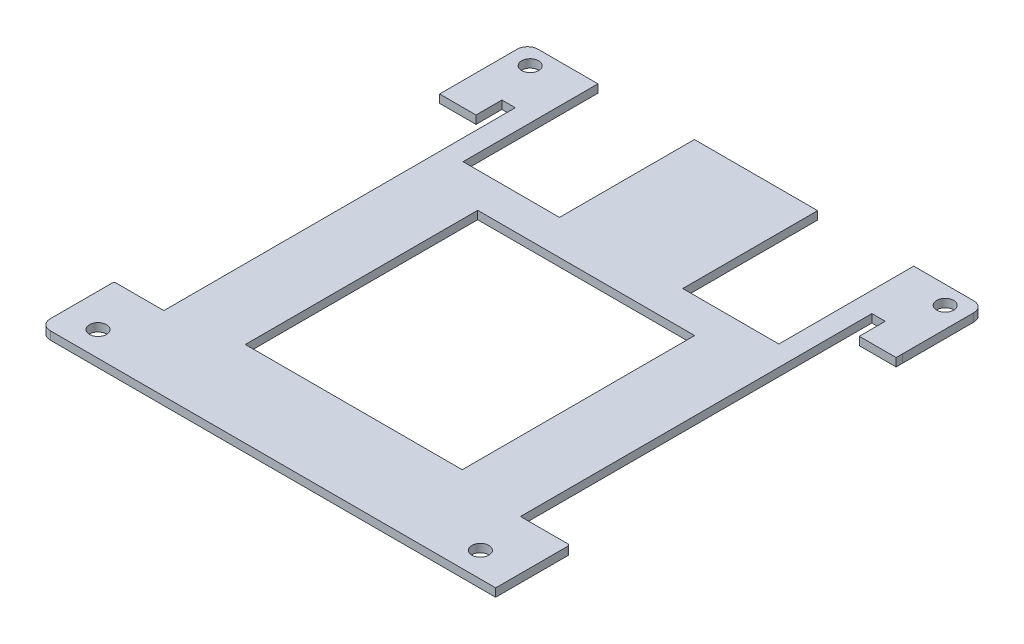
SolidWorks part; units mm, degrees
material "Copper"
ref_plane "Front Plane" through (0, 0, 0) normal (0, 0, 1) x (1, 0, 0)
ref_plane "Top Plane" through (0, 0, 0) normal (0, 1, 0) x (1, 0, 0)
ref_plane "Right Plane" through (0, 0, 0) normal (1, 0, 0) x (0, 0, -1)
sketch "Sketch1" plane through (0, 0, 0) normal (0, 1, 0) x (1, 0, 0)
  line L0 (-44, 45) -> (-44, 29.1624)
  line L1 (-43.6121, 28.7745) -> (-33.2119, 28.7745)
  line L2 (-42, 47) -> (42, 47)
  line L3 (44, 45) -> (44, 31.284)
  line L4 (32.8228, 27.7745) -> (32.8228, -30.4694)
  line L5 (26.2188, 17.9319) -> (-33.6927, 17.9319) construction
  line L6 (33.8228, 28.7745) -> (43.6111, 28.7745)
  line L7 (43.8497, -38.27) -> (43.8497, -47)
  line L8 (42.7059, -47) -> (-42, -47)
  line L9 (-44, -45) -> (-44, -38.977)
  line L10 (-32.824, 28.3866) -> (-32.824, -32.3056)
  line L11 (33.824, -32.6935) -> (36.0988, -32.6935)
  line L12 (23.409, -31.5) -> (-23.409, -31.5)
  line L13 (-23.409, -31.5) -> (-23.409, 13.2954)
  line L14 (-23.409, 13.2954) -> (-12.909, 13.2954)
  line L15 (-12.909, 13.2954) -> (-12.909, 25.9954)
  line L16 (-12.909, 25.9954) -> (12.909, 25.9954)
  line L17 (12.909, 25.9954) -> (12.909, 13.2954)
  line L18 (12.909, 13.2954) -> (23.409, 13.2954)
  line L19 (23.409, 13.2954) -> (23.409, -31.5)
  line L20 (43.8497, -38.27) -> (43.8497, -33.0814)
  line L21 (43.4618, -32.6935) -> (36.0988, -32.6935)
  line L22 (43.8497, -47) -> (42.7059, -47)
  line L23 (-44, 28.7745) -> (52.9697, 28.7745) construction
  line L24 (44, 31.284) -> (43.999, 29.1622)
  line L25 (-33.2119, -32.6935) -> (-36.1, -32.6935)
  line L26 (-44, -38.977) -> (-44, -33.0814)
  line L27 (-43.6121, -32.6935) -> (-36.1, -32.6935)
  line L28 (32.8228, -30.4694) -> (32.8228, -32.6935)
  line L29 (32.8228, -32.6935) -> (33.824, -32.6935)
  circle A0 centre (40, 43.5) radius 1.6383
  circle A1 centre (-40, 43.5) radius 1.6383
  circle A2 centre (-37.6, -42.2) radius 1.6383
  circle A3 centre (36.1, -42.2) radius 1.6383
  arc A5 (-42, 47) -> (-44, 45) centre (-42, 45) ccw
  arc A6 (44, 45) -> (42, 47) centre (42, 45) ccw
  arc A7 (-32.824, -32.3056) -> (-33.2119, -32.6935) centre (-33.2119, -32.3056) cw
  arc A10 (-33.2119, 28.7745) -> (-32.824, 28.3866) centre (-33.2119, 28.3866) cw
  arc A11 (-44, -45) -> (-42, -47) centre (-42, -45) ccw
  arc A12 (-44, 29.1624) -> (-43.6121, 28.7745) centre (-43.6121, 29.1624) ccw
  arc A13 (43.999, 29.1622) -> (43.6111, 28.7745) centre (43.6111, 29.1624) cw
  arc A14 (43.8497, -33.0814) -> (43.4618, -32.6935) centre (43.4618, -33.0814) ccw
  arc A15 (-44, -33.0814) -> (-43.6121, -32.6935) centre (-43.6121, -33.0814) cw
  arc A16 (33.8228, 28.7745) -> (32.8228, 27.7745) centre (33.8228, 27.7745) ccw
  point P27 (32.8228, -32.6935)
  point P51 (-32.824, -32.6935)
  point P54 (-32.824, 28.7745)
  point P60 (43.9988, 28.7745)
  point P67 (32.8228, 28.7745)
  dimension "D24" = 61.468
  dimension "D3" = 80
  dimension "D8" = 3.2766
  dimension "D22" = 1
  dimension "D2" = 6.4
  dimension "D4" = 44.7954
  dimension "D5" = 12.7
  dimension "D6" = 44.7954
  dimension "D7" = 3.5
  dimension "D9" = 4
  dimension "D10" = 3.5
  dimension "D11" = 85.7
  dimension "D12" = 85.7
  dimension "D13" = 21.0046
  dimension "D14" = 11.176
  dimension "D15" = 84
  dimension "D16" = 25.818
  dimension "D17" = 12.7
  dimension "D18" = 46.818
  dimension "D19" = 10.5
  dimension "D20" = 10.5
  dimension "D21" = 73.7
  dimension "D23" = 13.716
  dimension "D26" = 6.604
  dimension "D29" = 11.176
  dimension "D30" = 61.468
  dimension "D31" = 3.276
  dimension "D32" = 3.276
extrude "Boss-Extrude1" add sketch "Sketch1" along normal blind 1.575
sketch "Sketch2" plane through (0, 1.575, 0) normal (0, 1, 0) x (1, 0, 0)
  line L0 (-12.909, 19.06) -> (-30.435, 19.06)
  line L1 (42, 47) -> (-42, 47) construction
  line L2 (-12.909, 25.9954) -> (12.909, 25.9954) construction
  line L3 (-30.435, 47) -> (30.435, 47)
  line L4 (12.909, 13.2954) -> (12.909, 25.9954) construction
  line L5 (12.909, 19.06) -> (30.435, 19.06)
  line L6 (30.435, 19.06) -> (30.435, 47)
  line L7 (0, 47) -> (0, -47) construction
  line L8 (-42, -47) -> (43.8497, -47) construction
  line L9 (-12.909, 25.9954) -> (-12.909, 19.06)
  line L10 (-30.435, 19.06) -> (-30.435, 47)
  line L11 (12.909, 25.9954) -> (12.909, 19.06)
  line L13 (-12.909, 25.9954) -> (12.909, 25.9954)
  dimension "D1" = 27.94
  dimension "D2" = 17.526
extrude "Cut-Extrude1" cut sketch "Sketch2" against normal blind 2.54
sketch "Sketch16" plane through (0, 1.575, 0) normal (0, 1, 0) x (1, 0, 0)
  line L0 (-42, 47) -> (42, 47) construction
  line L1 (12.909, 19.06) -> (12.909, 13.2954)
  line L2 (12.909, 13.2954) -> (-12.909, 13.2954)
  line L3 (-11.8389, 47) -> (-11.8389, 21)
  line L4 (-30.435, 21) -> (-11.8389, 21)
  line L5 (11.909, 21) -> (11.909, 47)
  line L6 (11.909, 47) -> (-11.8389, 47)
  line L7 (-30.435, 47) -> (-30.435, 19.06) construction
  line L9 (-12.909, 19.06) -> (-12.909, 13.2954)
  line L10 (-30.435, 47) -> (-42, 47) construction
  line L11 (11.909, 21) -> (30.435, 21)
  line L12 (30.435, 19.06) -> (30.435, 47) construction
  line L13 (30.435, 21) -> (30.435, 19.06)
  line L14 (30.435, 19.06) -> (12.909, 19.06)
  line L15 (-30.435, 21) -> (-30.435, 19.06)
  line L16 (-30.435, 19.06) -> (-12.909, 19.06)
  dimension "D1" = 26
extrude "Cutouts for Thruster Heads" add sketch "Sketch16" against normal blind 1.575
sketch "Sketch17" plane through (0, 1.575, 0) normal (0, 1, 0) x (1, 0, 0)
  line L2 (-42.6204, -10.5244) -> (-42.6204, -23.1918)
  line L3 (-42.6204, -23.1918) -> (43.1801, -23.1918)
  line L4 (43.1801, -10.5244) -> (43.1801, -23.1918)
  line L6 (-42.6204, -10.5244) -> (-42.6204, 5.0143)
  line L7 (-42.6204, 5.0143) -> (43.1801, 5.0143)
  line L8 (43.1801, -10.5244) -> (43.1801, 5.0143)
sketch "Sketch18" plane through (0, 1.575, 0) normal (0, 1, 0) x (1, 0, 0)
  line L1 (33.4307, -29.0671) -> (45.3514, -29.0671)
  line L2 (33.4307, -29.0671) -> (33.4307, -32.653)
  line L3 (33.4307, -32.653) -> (45.3514, -32.653)
  line L4 (45.3514, -29.0671) -> (45.3514, -32.653)
  dimension "D1" = 14.347
  dimension "D2" = 10.419
sketch "Sketch21" [suppressed] plane through (0, 1.575, 0) normal (0, 1, 0) x (1, 0, 0)
  line L0 (-32.824, 28.3866) -> (-32.824, -32.3056) construction
  line L1 (-32.824, -23.1918) -> (32.8228, -23.1918)
  line L2 (-32.824, -23.1918) -> (-32.824, -25.8658)
  line L3 (-32.824, -25.8658) -> (32.8228, -25.8658)
  line L4 (32.8228, -23.1918) -> (32.8228, -25.8658)
  dimension "D1" = 2.674
sketch "Sketch20" plane through (0, 1.575, 0) normal (0, 1, 0) x (1, 0, 0)
sketch "Notch for BPR (TOP VIEW)" plane through (0, 1.575, 0) normal (0, 1, 0) x (1, 0, 0)
  line L0 (-43.6121, 28.7745) -> (-33.2119, 28.7745) construction
  line L1 (-36.984, 35.0445) -> (-34.409, 35.0445)
  line L2 (-36.984, 35.0445) -> (-36.984, 28.7745)
  line L3 (-36.984, 28.7745) -> (-34.409, 28.7745)
  line L4 (-34.409, 35.0445) -> (-34.409, 28.7745)
  line L6 (-44, 45) -> (-44, 29.1624) construction
  dimension "D1" = 7.016
  dimension "D2" = 2.575
  dimension "D3" = 6.27
extrude "Cut-Extrude11" cut sketch "Notch for BPR (TOP VIEW)" against normal blind 10
sketch "Notch for BPL (TOP VIEW)" plane through (0, 1.575, 0) normal (0, 1, 0) x (1, 0, 0)
  line L0 (33.8228, 28.7745) -> (43.6111, 28.7745) construction
  line L1 (34.3242, 35.0445) -> (36.8992, 35.0445)
  line L2 (34.3242, 35.0445) -> (34.3242, 28.7745)
  line L3 (34.3242, 28.7745) -> (36.8992, 28.7745)
  line L4 (36.8992, 35.0445) -> (36.8992, 28.7745)
  line L5 (44, 31.284) -> (44, 45) construction
  dimension "D1" = 2.575
  dimension "D2" = 7.1008
extrude "Cut-Extrude12" cut sketch "Notch for BPL (TOP VIEW)" against normal through all
sketch "Sketch22" plane through (0, 1.575, 0) normal (0, 1, 0) x (1, 0, 0)
  line L0 (-32.824, -32.3056) -> (-32.824, -38.5911) construction
  line L1 (34.3242, 28.7745) -> (32.8228, 28.7745)
  line L2 (34.3242, 28.7745) -> (34.3242, -32.6935)
  line L3 (34.3242, -32.6935) -> (32.8228, -32.6935)
  line L4 (32.8228, 28.7745) -> (32.8228, -32.6935)
  line L5 (-33.2119, -32.6935) -> (-31.5595, -32.6935) construction
  line L7 (-32.824, -32.6935) -> (-34.409, -32.6935)
  line L8 (-32.824, -32.6935) -> (-32.824, 28.7745)
  line L9 (-32.824, 28.7745) -> (-34.409, 28.7745)
  line L10 (-34.409, -32.6935) -> (-34.409, 28.7745)
extrude "Boss-Extrude2" add sketch "Sketch22" against normal blind 1.575
sketch "Sketch23" plane through (0, 1.575, 0) normal (0, 1, 0) x (1, 0, 0)
  line L0 (43.999, 29.1622) -> (44, 31.284) construction
  line L1 (36.8992, 28.7745) -> (43.9994, 28.7745)
  line L2 (36.8992, 28.7745) -> (36.8992, 30.0445)
  line L3 (36.8992, 30.0445) -> (43.9994, 30.0445)
  line L4 (43.9994, 28.7745) -> (43.9994, 30.0445)
  line L5 (-44, 45) -> (-44, 29.1624) construction
  line L6 (-36.984, 28.7745) -> (-44, 28.7745)
  line L7 (-36.984, 28.7745) -> (-36.984, 30.0445)
  line L8 (-36.984, 30.0445) -> (-44, 30.0445)
  line L9 (-44, 28.7745) -> (-44, 30.0445)
  dimension "D1" = 1.27
  dimension "D2" = 1.27
extrude "Cut-Extrude13" cut sketch "Sketch23" against normal through all
sketch "Sketch25" plane through (0, 1.575, 0) normal (0, 1, 0) x (1, 0, 0)
  line L0 (23.409, 13.2954) -> (-23.409, 13.2954) construction
  line L1 (23.409, -31.5) -> (20.909, -31.5)
  line L2 (23.409, -31.5) -> (23.409, 13.2954)
  line L3 (23.409, 13.2954) -> (20.909, 13.2954)
  line L4 (20.909, -31.5) -> (20.909, 13.2954)
  dimension "D1" = 2.5
extrude "Boss-Extrude3" add sketch "Sketch25" against normal blind 1.575
sketch "Sketch26" plane through (0, 1.575, 0) normal (0, 1, 0) x (1, 0, 0)
  line L0 (20.909, 13.2954) -> (-23.409, 13.2954) construction
  line L1 (-23.409, -31.5) -> (-20.909, -31.5)
  line L2 (-23.409, -31.5) -> (-23.409, 13.2954)
  line L3 (-23.409, 13.2954) -> (-20.909, 13.2954)
  line L4 (-20.909, -31.5) -> (-20.909, 13.2954)
  dimension "D1" = 2.5
extrude "Boss-Extrude4" add sketch "Sketch26" against normal blind 1.575
sketch "Sketch27" plane through (0, 1.575, 0) normal (0, 1, 0) x (1, 0, 0)
  line L1 (-20.909, 13.2954) -> (20.909, 13.2954)
  line L2 (-20.909, 13.2954) -> (-20.909, 14.2954)
  line L3 (-20.909, 14.2954) -> (20.909, 14.2954)
  line L4 (20.909, 13.2954) -> (20.909, 14.2954)
  dimension "D1" = 1
extrude "Cut-Extrude15" cut sketch "Sketch27" against normal through all
sketch "Sketch28" plane through (0, 1.575, 0) normal (0, 1, 0) x (1, 0, 0)
  line L0 (20.909, 14.2954) -> (20.909, -31.5) construction
  line L1 (-20.909, -31.5) -> (20.909, -31.5)
  line L2 (-20.909, -31.5) -> (-20.909, -30.5)
  line L3 (-20.909, -30.5) -> (20.909, -30.5)
  line L4 (20.909, -31.5) -> (20.909, -30.5)
  dimension "D1" = 1
extrude "Boss-Extrude5" add sketch "Sketch28" against normal blind 1.575
